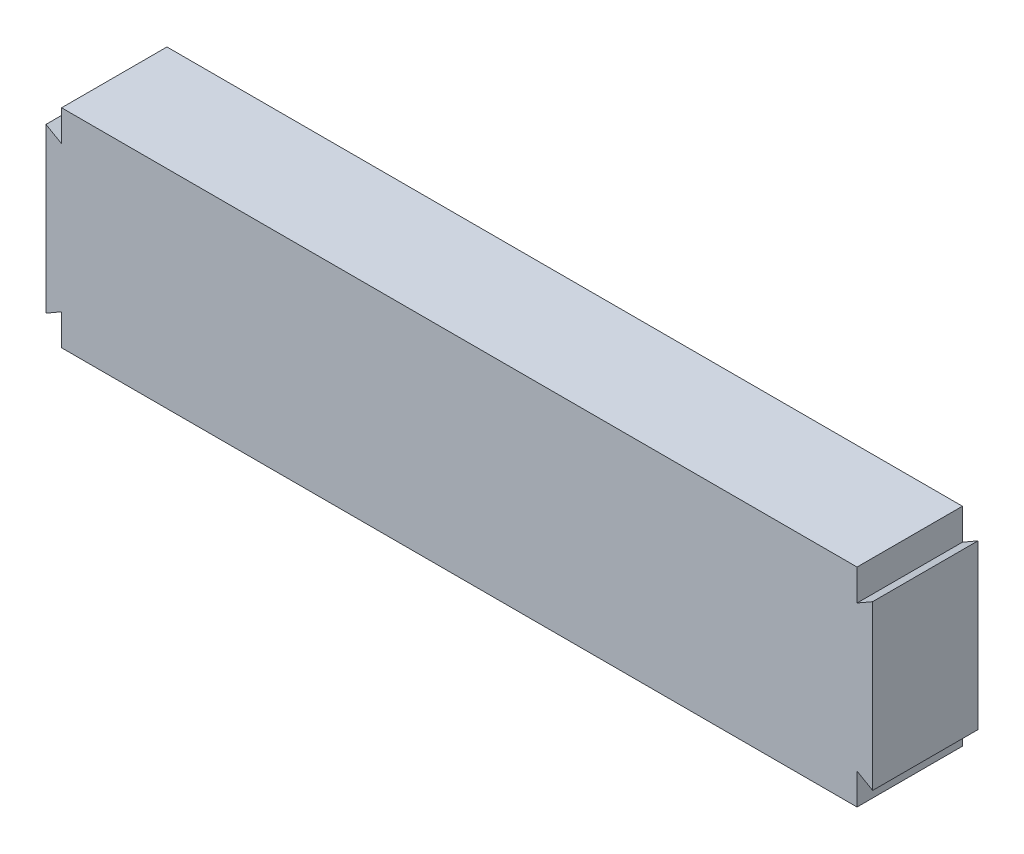
SolidWorks part; units mm, degrees
ref_plane "Front Plane" through (0, 0, 0) normal (0, 0, 1) x (1, 0, 0)
ref_plane "Top Plane" through (0, 0, 0) normal (0, 1, 0) x (1, 0, 0)
ref_plane "Right Plane" through (0, 0, 0) normal (1, 0, 0) x (0, 0, -1)
sketch "Sketch1" plane through (0, 0, 0) normal (0, 0, 1) x (1, 0, 0)
  line L24 (-37.8434, -19.932) -> (37.6566, -19.932)
  line L25 (37.6566, -19.932) -> (37.6566, -16.9724)
  line L26 (37.6566, -16.9724) -> (39.1364, -17.8268)
  line L27 (39.1364, -17.8268) -> (39.1364, -2.3066)
  line L28 (39.1364, -2.3066) -> (37.6566, -3.1609)
  line L29 (37.6566, -3.1609) -> (37.6566, -0.2013)
  line L30 (37.6566, -0.2013) -> (-37.8434, -0.2013)
  line L31 (-37.8434, -0.2013) -> (-37.8434, -3.1609)
  line L32 (-37.8434, -3.1609) -> (-39.3232, -2.3066)
  line L33 (-39.3232, -2.3066) -> (-39.3232, -17.8268)
  line L34 (-39.3232, -17.8268) -> (-37.8434, -16.9724)
  line L35 (-37.8434, -16.9724) -> (-37.8434, -19.932)
  dimension "D1" = 75.5
  dimension "D2" = 15.5202
  dimension "D3" = 60
  dimension "D4" = 60
  dimension "D5" = 60
  dimension "D6" = 60
extrude "Boss-Extrude1" add sketch "Sketch1" along normal blind 10
